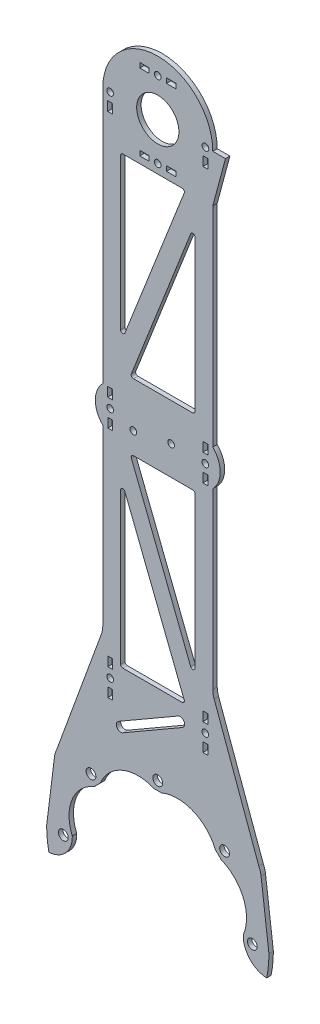
SolidWorks part; units mm, degrees
ref_plane "前视基准面" through (0, 0, 0) normal (0, 0, 1) x (1, 0, 0)
ref_plane "上视基准面" through (0, 0, 0) normal (0, 1, 0) x (1, 0, 0)
ref_plane "右视基准面" through (0, 0, 0) normal (1, 0, 0) x (0, 0, -1)
sketch "草图1" plane through (0, 0, 0) normal (0, 0, 1) x (1, 0, 0)
  line L0 (0, -125) -> (0, 175) construction
  line L3 (37.1881, -134.9645) -> (48.997, -134.9645) construction
  line L4 (0, -125) -> (-38.5, -125) construction
  line L5 (0, -125) -> (42.5, -125) construction
  line L6 (-37.1881, -134.9645) -> (-48.997, -134.9645) construction
  line L12 (-24.7418, 0) -> (-24.7418, 174.9968) construction
  line L14 (0, 175) -> (3.9, 175) construction
  line L17 (-3.9, 157.8791) -> (3.9, 157.8791) construction
  line L22 (-3.9, 191.0209) -> (-8.1, 193.2209) construction
  line L24 (-3.9, 156.7791) -> (-8.1, 158.9791) construction
  line L33 (46.4614, -96.4475) -> (50, -125)
  line L34 (10.0565, 145.5707) -> (-10.0565, 133.9585) construction
  line L37 (3.9, 193.2209) -> (8.1, 193.2209)
  line L38 (3.9, 193.2209) -> (3.9, 191.0209)
  line L39 (3.9, 191.0209) -> (8.1, 191.0209)
  line L40 (8.1, 193.2209) -> (8.1, 191.0209)
  line L41 (3.9, 193.2209) -> (8.1, 191.0209) construction
  line L42 (3.9, 191.0209) -> (8.1, 193.2209) construction
  line L43 (-46.4614, -96.4475) -> (-50, -125)
  line L46 (3.9, 158.9791) -> (8.1, 156.7791) construction
  line L47 (-42.5, -122.8) -> (0, -125) construction
  line L52 (11.0565, 143.8387) -> (-9.0565, 132.2264) construction
  line L53 (24.7418, 0) -> (24.7418, 37.3055)
  line L54 (0, -125) -> (-42.5, -127.2) construction
  line L55 (0, -125) -> (-31.5251, -96.582) construction
  line L56 (0, -125) -> (-28.4567, -93.4331) construction
  line L57 (-30.052, -94.948) -> (0, -125) construction
  line L58 (-3.9, 193.2209) -> (-8.1, 191.0209) construction
  line L59 (-8.1, 193.2209) -> (-8.1, 191.0209)
  line L60 (-3.9, 191.0209) -> (-8.1, 191.0209)
  line L61 (-3.9, 193.2209) -> (-3.9, 191.0209)
  line L62 (-3.9, 193.2209) -> (-8.1, 193.2209)
  line L63 (-3.9, 192.1209) -> (3.9, 192.1209) construction
  line L64 (22.4921, -49.4354) -> (20.2921, -49.4354)
  line L69 (22.4921, 47.7646) -> (22.4921, 43.5646)
  line L70 (-20.2921, 47.7646) -> (-22.4921, 43.5646) construction
  line L71 (-22.548, 55.5646) -> (-22.548, 59.7646)
  line L76 (-22.548, 55.5646) -> (-20.348, 55.5646)
  line L78 (9.0565, 147.3028) -> (-11.0565, 135.6905) construction
  line L79 (3.9, 156.7791) -> (8.1, 158.9791) construction
  line L80 (-3.9, 158.9791) -> (-8.1, 156.7791) construction
  line L81 (-3.9, 156.7791) -> (-8.1, 156.7791)
  line L82 (-3.9, 156.7791) -> (-3.9, 158.9791)
  line L83 (-3.9, 158.9791) -> (-8.1, 158.9791)
  line L84 (-8.1, 156.7791) -> (-8.1, 158.9791)
  line L85 (8.1, 156.7791) -> (8.1, 158.9791)
  line L86 (3.9, 158.9791) -> (8.1, 158.9791)
  line L87 (3.9, 156.7791) -> (3.9, 158.9791)
  line L88 (3.9, 156.7791) -> (8.1, 156.7791)
  line L89 (-16.7418, 38.5646) -> (16.7418, -46.6009) construction
  line L92 (-20.2921, -57.2354) -> (-22.4921, -61.4354) construction
  line L93 (-22.4921, -49.4354) -> (-22.4921, -45.2354)
  line L94 (-22.4921, -49.4354) -> (-20.2921, -49.4354)
  line L95 (-20.2921, -49.4354) -> (-20.2921, -45.2354)
  line L96 (-22.4921, -45.2354) -> (-20.2921, -45.2354)
  line L97 (-22.4921, -49.4354) -> (-20.2921, -45.2354) construction
  line L98 (-20.2921, -49.4354) -> (-22.4921, -45.2354) construction
  line L99 (-22.4921, -57.2354) -> (-20.2921, -61.4354) construction
  line L100 (-22.4921, -61.4354) -> (-20.2921, -61.4354)
  line L101 (-20.2921, -57.2354) -> (-20.2921, -61.4354)
  line L102 (-22.4921, -57.2354) -> (-20.2921, -57.2354)
  line L103 (-22.4921, -57.2354) -> (-22.4921, -61.4354)
  line L104 (20.2921, -49.4354) -> (20.2921, -45.2354)
  line L105 (-20.348, 55.5646) -> (-20.348, 59.7646)
  line L106 (-22.548, 59.7646) -> (-20.348, 59.7646)
  line L107 (-22.548, 55.5646) -> (-20.348, 59.7646) construction
  line L108 (-20.348, 55.5646) -> (-22.548, 59.7646) construction
  line L109 (-22.4921, 47.7646) -> (-20.2921, 43.5646) construction
  line L110 (-22.4921, 43.5646) -> (-20.2921, 43.5646)
  line L111 (-20.2921, 47.7646) -> (-20.2921, 43.5646)
  line L120 (10.0565, -54.6009) -> (-16.6669, -70.0297) construction
  line L123 (-22.4921, 47.7646) -> (-20.2921, 47.7646)
  line L124 (-22.4921, 47.7646) -> (-22.4921, 43.5646)
  line L125 (22.4921, 47.7646) -> (20.2921, 47.7646)
  line L126 (-16.7418, -46.6009) -> (16.7418, -46.6009) construction
  line L131 (-16.7418, -46.6009) -> (-16.7418, 38.5646) construction
  line L132 (-16.7418, 38.5646) -> (16.7418, 38.5646) construction
  line L133 (16.7418, -46.6009) -> (16.7418, 38.5646) construction
  line L138 (20.2921, 47.7646) -> (20.2921, 43.5646)
  line L139 (11.0565, -56.333) -> (-15.6669, -71.7617)
  line L140 (9.0565, -52.8689) -> (-17.6669, -68.2976)
  line L141 (24.7418, 37.3055) -> (24.7418, 66.0208) construction
  line L142 (-30.0233, 61.4139) -> (23.0071, -73.4688) construction
  line L147 (22.4921, -45.2354) -> (20.2921, -45.2354)
  line L148 (22.4921, -49.4354) -> (22.4921, -45.2354)
  line L149 (22.4921, -57.2354) -> (22.4921, -61.4354)
  line L150 (22.4921, -57.2354) -> (20.2921, -57.2354)
  line L151 (20.2921, -57.2354) -> (20.2921, -61.4354)
  line L152 (22.4921, -61.4354) -> (20.2921, -61.4354)
  line L153 (22.4921, 43.5646) -> (20.2921, 43.5646)
  line L154 (22.548, 55.5646) -> (20.348, 55.5646)
  line L155 (20.348, 55.5646) -> (20.348, 59.7646)
  line L156 (22.548, 59.7646) -> (20.348, 59.7646)
  line L157 (22.548, 55.5646) -> (22.548, 59.7646)
  line L166 (21.448, 131.6646) -> (21.448, 175) construction
  line L171 (22.548, 171.1) -> (22.548, 166.9)
  line L172 (22.548, 171.1) -> (20.348, 171.1)
  line L173 (20.348, 171.1) -> (20.348, 166.9)
  line L174 (22.548, 166.9) -> (20.348, 166.9)
  line L175 (-22.548, 166.9) -> (-20.348, 166.9)
  line L176 (-20.348, 171.1) -> (-20.348, 166.9)
  line L177 (-22.548, 171.1) -> (-20.348, 171.1)
  line L178 (-22.548, 171.1) -> (-22.548, 166.9)
  line L179 (-22.578, 64.341) -> (30.4524, -70.5417) construction
  line L180 (-16.7418, 22.356) -> (-16.7418, -45.6009)
  line L181 (-15.7418, -46.6009) -> (10.9761, -46.6009)
  line L182 (11.9067, -45.235) -> (-14.8112, 22.7219)
  line L183 (-10.9761, 38.5646) -> (15.7418, 38.5646)
  line L184 (16.7418, 37.5646) -> (16.7418, -30.3923)
  line L185 (14.8112, -30.7582) -> (-11.9067, 37.1987)
  line L186 (0, 53.5646) -> (-8.1, 53.5646) construction
  line L191 (16.7418, 153.7301) -> (16.7418, 68.5646) construction
  line L192 (-16.7418, 68.5646) -> (16.7418, 68.5646) construction
  line L193 (-16.7418, 153.7301) -> (-16.7418, 68.5646) construction
  line L194 (-16.7418, 153.7301) -> (16.7418, 153.7301) construction
  line L195 (-16.7418, 68.5646) -> (16.7418, 153.7301) construction
  line L196 (14.8112, 137.8874) -> (-11.9067, 69.9305)
  line L197 (16.7418, 69.5646) -> (16.7418, 137.5215)
  line L198 (-10.9761, 68.5646) -> (15.7418, 68.5646)
  line L199 (11.9067, 152.3642) -> (-14.8112, 84.4073)
  line L200 (-15.7418, 153.7301) -> (10.9761, 153.7301)
  line L201 (-16.7418, 84.7732) -> (-16.7418, 152.7301)
  line L202 (-24.7418, 0) -> (-24.7418, -20.2354)
  line L204 (24.7418, -20.2354) -> (24.7418, 0)
  line L206 (24.7418, 59.7646) -> (24.7418, 66.0208)
  line L207 (24.7418, 43.5646) -> (24.7418, 37.3055)
  line L208 (-24.7418, 59.7646) -> (-24.7418, 174.9968)
  line L209 (-24.7418, 43.5646) -> (-24.7418, 0)
  line L210 (-24.7418, -20.2354) -> (-24.7418, -34.666)
  line L211 (24.7418, -20.2354) -> (24.7418, -34.666)
  line L212 (45.481, -93.204) -> (25.349, -38.0974)
  line L213 (-25.349, -38.0974) -> (-45.481, -93.204)
  line L214 (24.7418, 174.9968) -> (24.7418, 190) construction
  line L215 (24.7418, 190) -> (19.6763, 190) construction
  line L216 (24.7418, 174.9968) -> (30.4524, 174.9968)
  line L217 (30.4524, 174.9968) -> (24.7418, 153.7301)
  line L218 (24.7418, 153.7301) -> (24.7418, 66.0208)
  circle A13 centre (0, -125) radius 42.5 construction
  circle A14 centre (0, -167.5) radius 2.2 construction
  circle A15 centre (-30.052, -155.052) radius 2.2 construction
  circle A16 centre (-42.5, -125) radius 2.2
  circle A17 centre (-30.052, -94.948) radius 2.2
  circle A18 centre (0, -82.5) radius 2.2
  circle A19 centre (30.052, -94.948) radius 2.2
  circle A20 centre (42.5, -125) radius 2.2
  circle A21 centre (30.052, -155.052) radius 2.2 construction
  arc A24 (-50, -125) -> (50, -125) centre (0, -125) ccw construction
  arc A26 (-37.1881, -134.9645) -> (37.1881, -134.9645) centre (0, -125) cw construction
  arc A27 (-50, -125) -> (-48.2963, -137.941) centre (0, -125) ccw construction
  circle A33 centre (0, 174.9968) radius 9.5
  circle A43 centre (0, 175) radius 35.5 construction
  arc A48 (-38.4655, -123.3708) -> (-28.4746, -99.0877) centre (-21.4862, -116.1598) cw
  arc A49 (-1.6292, -86.5345) -> (-25.9123, -96.5254) centre (-8.8402, -103.5138) ccw
  arc A50 (1.6292, -86.5345) -> (25.9123, -96.5254) centre (8.8402, -103.5138) cw
  arc A51 (38.4655, -123.3708) -> (28.4746, -99.0877) centre (21.4862, -116.1598) ccw
  arc A52 (-38.4485, -126.9903) -> (-38.4655, -123.3708) centre (0, -125) cw construction
  arc A53 (-28.4746, -99.0877) -> (-25.9123, -96.5254) centre (0, -125) cw
  arc A54 (-1.6292, -86.5345) -> (1.6292, -86.5345) centre (0, -125) cw
  arc A55 (25.9123, -96.5254) -> (28.4746, -99.0877) centre (0, -125) cw
  arc A56 (38.4655, -123.3708) -> (37.1881, -134.9645) centre (0, -125) cw construction
  arc A57 (-38.4485, -126.9903) -> (-37.1881, -134.9645) centre (0, -125) ccw construction
  circle A58 centre (0, 192.1209) radius 1.5
  arc A60 (50, -125) -> (48.997, -134.9645) centre (0, -125) cw
  arc A61 (-50, -125) -> (-48.997, -134.9645) centre (0, -125) ccw
  arc A65 (11.0565, 143.8387) -> (9.0565, 147.3028) centre (10.0565, 145.5707) ccw construction
  arc A66 (-11.0565, 135.6905) -> (-9.0565, 132.2264) centre (-10.0565, 133.9585) ccw construction
  circle A69 centre (0, 157.8791) radius 1.5
  circle A70 centre (-21.3921, -53.3354) radius 1.5
  circle A74 centre (-21.3921, 51.6646) radius 1.5
  arc A77 (-38.4655, -123.3708) -> (-48.997, -134.9645) centre (-49.6309, -123.8085) cw
  arc A78 (48.997, -134.9645) -> (38.4655, -123.3708) centre (49.6309, -123.8085) cw
  arc A79 (11.0565, -56.333) -> (9.0565, -52.8689) centre (10.0565, -54.6009) ccw
  arc A80 (-17.6669, -68.2976) -> (-15.6669, -71.7617) centre (-16.6669, -70.0297) ccw
  circle A85 centre (21.3921, -53.3354) radius 1.5
  circle A86 centre (21.3921, 51.6646) radius 1.5
  circle A89 centre (21.448, 175) radius 1.5
  circle A90 centre (-21.448, 175) radius 1.5
  circle A91 centre (0, 53.5646) radius 1.5 construction
  arc A92 (-14.8112, 22.7219) -> (-16.7418, 22.356) centre (-15.7418, 22.356) ccw
  arc A93 (-16.7418, -45.6009) -> (-15.7418, -46.6009) centre (-15.7418, -45.6009) ccw
  arc A94 (10.9761, -46.6009) -> (11.9067, -45.235) centre (10.9761, -45.6009) ccw
  arc A95 (-10.9761, 38.5646) -> (-11.9067, 37.1987) centre (-10.9761, 37.5646) ccw
  arc A96 (16.7418, 37.5646) -> (15.7418, 38.5646) centre (15.7418, 37.5646) ccw
  arc A97 (16.7418, -30.3923) -> (14.8112, -30.7582) centre (15.7418, -30.3923) cw
  arc A98 (16.7418, 137.5215) -> (14.8112, 137.8874) centre (15.7418, 137.5215) ccw
  arc A99 (16.7418, 69.5646) -> (15.7418, 68.5646) centre (15.7418, 69.5646) cw
  arc A100 (-10.9761, 68.5646) -> (-11.9067, 69.9305) centre (-10.9761, 69.5646) cw
  arc A101 (10.9761, 153.7301) -> (11.9067, 152.3642) centre (10.9761, 152.7301) cw
  arc A102 (-16.7418, 152.7301) -> (-15.7418, 153.7301) centre (-15.7418, 152.7301) cw
  arc A103 (-14.8112, 84.4073) -> (-16.7418, 84.7732) centre (-15.7418, 84.7732) cw
  arc A106 (24.7418, 59.7646) -> (24.7418, 43.5646) centre (16.6418, 51.6646) cw
  arc A107 (-24.7418, 59.7646) -> (-24.7418, 43.5646) centre (-16.6418, 51.6646) ccw
  arc A110 (-46.4614, -96.4475) -> (-45.481, -93.204) centre (-36.5373, -97.6774) cw
  arc A111 (46.4614, -96.4475) -> (45.481, -93.204) centre (36.5373, -97.6774) ccw
  arc A112 (-25.349, -38.0974) -> (-24.7418, -34.666) centre (-34.7418, -34.666) ccw
  arc A113 (25.349, -38.0974) -> (24.7418, -34.666) centre (34.7418, -34.666) cw
  arc A114 (-24.7418, 174.9968) -> (19.6763, 190) centre (0.0011, 174.9968) cw construction
  circle A115 centre (0.0011, 174.9968) radius 24.7429 construction
  arc A116 (-24.7418, 174.9968) -> (24.7418, 174.9968) centre (0, 174.9968) cw
  circle A117 centre (0, 175) radius 127.2354 construction
  circle A118 centre (-10.9761, 48.2389) radius 1.5
  circle A119 centre (6, 51.6646) radius 1.5
  point P2 (-3.3052, -62.3153)
  point P18 (-21.3921, 51.6646)
  point P56 (6, 192.1209)
  point P70 (-6, 157.8791)
  point P71 (6, 157.8791)
  point P77 (-21.3921, -47.3354)
  point P91 (0, 139.7646)
  point P118 (-6, 192.1209)
  point P126 (-21.448, 57.6646)
  point P133 (-21.3921, 45.6646)
  point P159 (-16.7418, 27.6325)
  point P168 (12.4438, -46.6009)
  point P171 (-12.4438, 38.5646)
  point P188 (16.7418, -35.6689)
  point P228 (16.7418, 142.7981)
  point P229 (-12.4438, 68.5646)
  point P230 (12.4438, 153.7301)
  point P231 (-16.7418, 79.4967)
  point P250 (-46.25, -94.7415)
  point P253 (46.25, -94.7415)
  dimension "D1" = 8
  dimension "D2" = 10
  dimension "D4" = 71
  dimension "D5" = 10
  dimension "D8" = 1
  dimension "D9" = 1
  dimension "D10" = 1
  dimension "D11" = 1
  dimension "D12" = 1
  dimension "D13" = 1
  dimension "D14" = 10
  dimension "D15" = 10
  dimension "D3" = 15
  dimension "D6" = 4
  dimension "D7" = 8
extrude "凸台-拉伸1" add sketch "草图1" along normal blind 2
